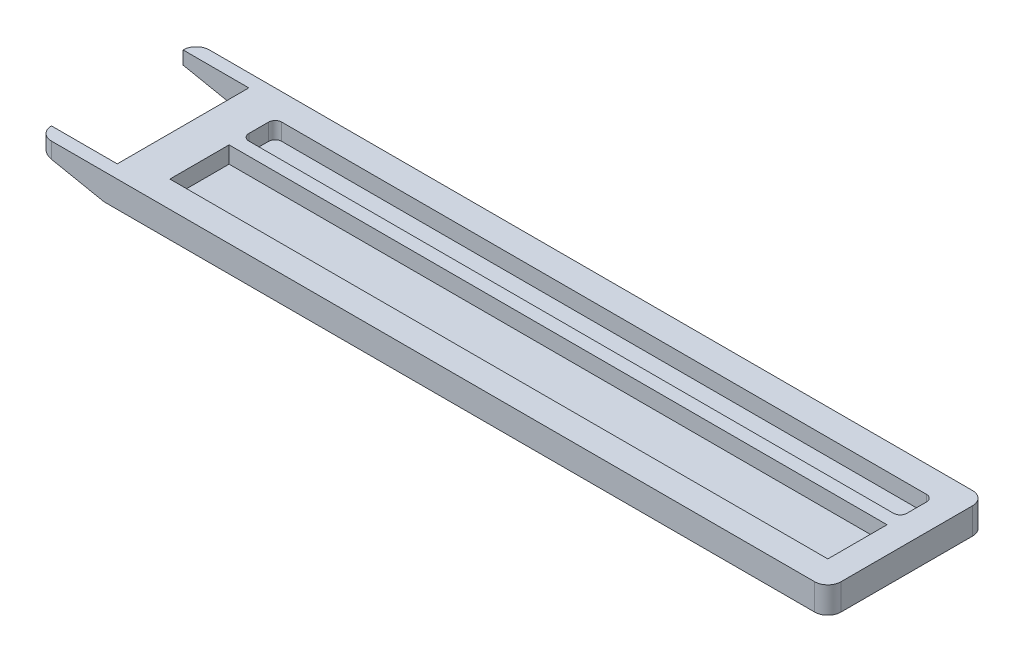
SolidWorks part; units mm, degrees
material "1060 Alloy"
ref_plane "Front Plane" through (0, 0, 0) normal (0, 0, 1) x (1, 0, 0)
ref_plane "Top Plane" through (0, 0, 0) normal (0, 1, 0) x (1, 0, 0)
ref_plane "Right Plane" through (0, 0, 0) normal (1, 0, 0) x (0, 0, -1)
sketch "Sketch1" plane through (0, 0, 0) normal (0, 1, 0) x (1, 0, 0)
  line L1 (300, -60) -> (-300, -60)
  line L2 (300, -60) -> (300, 60)
  line L3 (300, 60) -> (-300, 60)
  line L4 (-300, -60) -> (-300, 60)
  line L5 (300, -60) -> (-300, 60) construction
  line L6 (300, 60) -> (-300, -60) construction
  point P0 (0, 0)
  dimension "D1" = 120
  dimension "D2" = 600
extrude "Boss-Extrude1" add sketch "Sketch1" along normal blind 20
sketch "Sketch4" plane through (0, 0, 60) normal (0, 0, 1) x (1, 0, 0)
  line L0 (-300, 10) -> (-250, 0)
  line L1 (-300, 20) -> (-300, 0) construction
  line L2 (-300, 0) -> (300, 0) construction
  line L3 (-250, 0) -> (-300, 0)
  line L4 (-300, 0) -> (-300, 10)
  dimension "D1" = 50
extrude "Cut-Extrude1" cut sketch "Sketch4" against normal up to next
sketch "Sketch6" plane through (0, 20, 0) normal (0, 1, 0) x (1, 0, 0)
  line L0 (300, 60) -> (-300, 60) construction
  line L1 (-220, 40) -> (280, 40)
  line L2 (-220, 40) -> (-220, 15)
  line L3 (-220, 15) -> (280, 15)
  line L4 (280, 40) -> (280, 15)
  line L5 (300, -60) -> (300, 60) construction
  line L6 (-300, -60) -> (300, -60) construction
  line L7 (-220, 5) -> (280, 5)
  line L8 (-220, 5) -> (-220, -40)
  line L9 (-220, -40) -> (280, -40)
  line L10 (280, 5) -> (280, -40)
  dimension "D1" = 25
  dimension "D2" = 500
  dimension "D3" = 20
  dimension "D4" = 20
  dimension "D5" = 500
  dimension "D6" = 45
  dimension "D7" = 20
  dimension "D8" = 20
extrude "Cut-Extrude2" cut sketch "Sketch6" against normal blind 12.7
fillet "Fillet1" radius 10 4 edges at (-300, 15, -60) (-300, 15, 60) (300, 10, -60) (300, 10, 60)
fillet "Fillet2" radius 5 4 edges at (280, 13.65, -15) (280, 13.65, -40) (-220, 13.65, -15) (-220, 13.65, -40)
sketch "Sketch7" plane through (0, 20, 0) normal (0, 1, 0) x (1, 0, 0)
  line L0 (-300, 50) -> (-300, -50) construction
  line L1 (-300, 50) -> (-250, 50)
  line L2 (-300, 50) -> (-300, -50)
  line L3 (-300, -50) -> (-250, -50)
  line L4 (-250, 50) -> (-250, -50)
  line L5 (290, 60) -> (-290, 60) construction
  line L6 (-290, -60) -> (290, -60) construction
  dimension "D1" = 10
  dimension "D2" = 10
  dimension "D3" = 50
extrude "Cut-Extrude3" cut sketch "Sketch7" against normal up to next
equation "\"forklenghth\"=600"
equation "\"D2@Sketch1\"=\"forklenghth\""
equation "\"W_guide\"=30"
equation "\"W_rail\"=25"
equation "\"D1@Sketch6\"=\"W_rail\""
equation "\"L_rail\"= 500"
equation "\"D2@Sketch6\"= \"L_rail\""
equation "\"L_rack\"= 500"
equation "\"D5@Sketch6\"=\"L_rack\""
equation "\"W_rack\"=45"
equation "\"D6@Sketch6\"=\"W_rack\""
